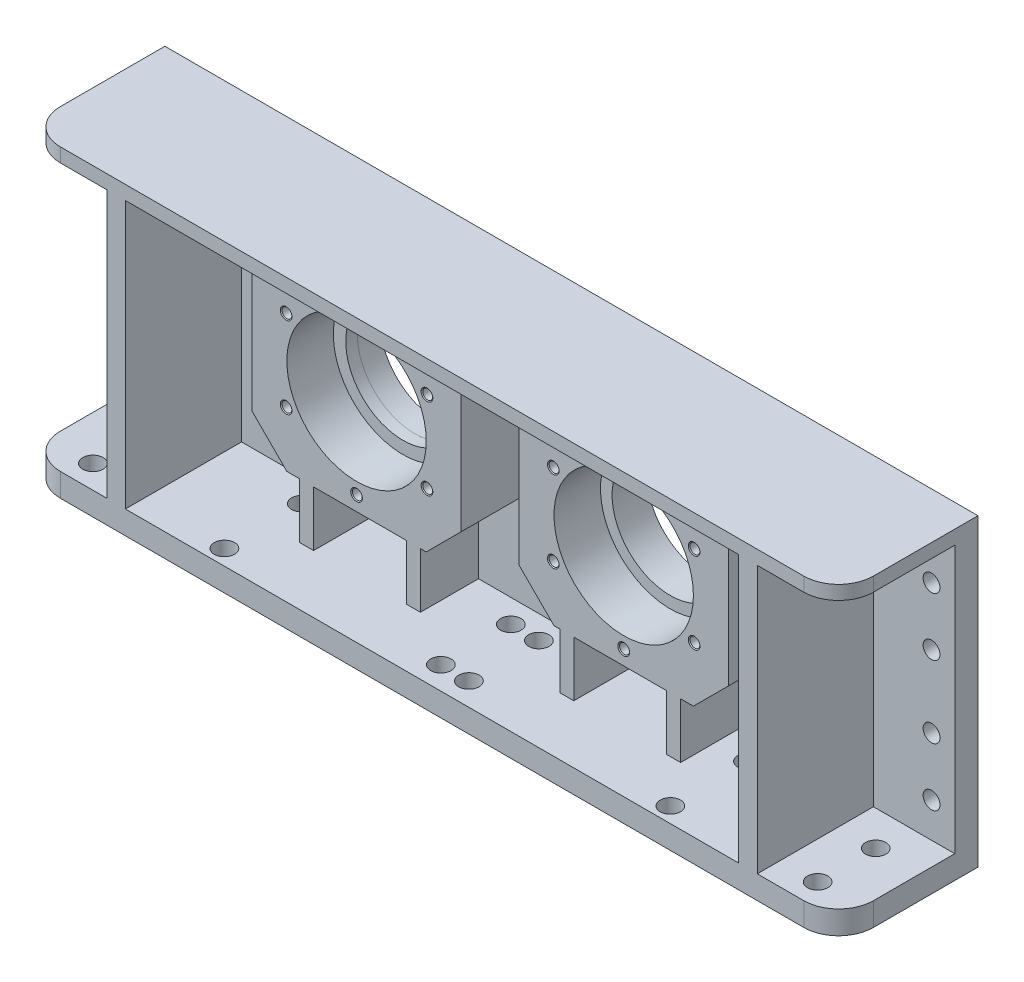
SolidWorks part; units mm, degrees
ref_plane "Front Plane" through (0, 0, 0) normal (0, 0, 1) x (1, 0, 0)
ref_plane "Top Plane" through (0, 0, 0) normal (0, 1, 0) x (1, 0, 0)
ref_plane "Right Plane" through (0, 0, 0) normal (1, 0, 0) x (0, 0, -1)
sketch "Sketch1" plane through (0, 0, 0) normal (0, 1, 0) x (1, 0, 0)
  line L0 (-55, 0) -> (55, 0) construction
  line L1 (-350, 0) -> (350, 0)
  line L2 (-350, 0) -> (-350, -120)
  line L3 (-350, -120) -> (350, -120)
  line L4 (350, 0) -> (350, -120)
  dimension "D1" = 700
  dimension "D2" = 350
  dimension "D3" = 120
extrude "Boss-Extrude1" add sketch "Sketch1" along normal blind 20
sketch "Sketch2" plane through (0, 0, 0) normal (0, 0, 1) x (1, 0, 0)
  line L1 (350, 20) -> (-350, 20)
  line L2 (350, 20) -> (350, 262)
  line L3 (350, 262) -> (-350, 262)
  line L4 (-350, 20) -> (-350, 262)
  dimension "D1" = 242
extrude "Boss-Extrude2" add sketch "Sketch2" along normal blind 20
sketch "Sketch3" plane through (0, 0, 20) normal (0, 0, 1) x (1, 0, 0)
  line L0 (350, 20) -> (350, 262) construction
  line L1 (-350, 262) -> (350, 262)
  line L2 (-350, 262) -> (-350, 250)
  line L3 (-350, 250) -> (350, 250)
  line L4 (350, 262) -> (350, 250)
  line L5 (-350, 20) -> (350, 20) construction
  line L6 (-280, 20) -> (-264, 20)
  line L7 (-280, 20) -> (-280, 250.6161)
  line L8 (-280, 250.6161) -> (-264, 250.6161)
  line L9 (-264, 20) -> (-264, 250.6161)
  line L10 (264, 20) -> (280, 20)
  line L11 (264, 20) -> (264, 251.2549)
  line L12 (264, 251.2549) -> (280, 251.2549)
  line L13 (280, 20) -> (280, 251.2549)
  line L14 (-350, 262) -> (-350, 20) construction
  line M11 (-350, 20) -> (350, 20)
  dimension "D1" = 12
  dimension "D2" = 16
  dimension "D3" = 16
  dimension "D4" = 70
  dimension "D5" = 70
extrude "Boss-Extrude3" add sketch "Sketch3" along normal up to surface (100 mm away) contours L13 L3 L11 M11 | L9 L8 L7 L6 up to face at (0, 10, 120)
sketch "Sketch4" plane through (0, 0, 20) normal (0, 0, 1) x (1, 0, 0)
  line L0 (-350, 0) -> (350, 0) construction
  line L1 (0, -66) -> (0, 66) construction
  circle A0 centre (-115, 150) radius 50
  circle A1 centre (115, 150) radius 50
  dimension "D1" = 100
  dimension "D2" = 100
  dimension "D3" = 150
  dimension "D4" = 150
  dimension "D5" = 115
  dimension "D6" = 115
extrude "Cut-Extrude1" cut sketch "Sketch4" against normal blind 30
sketch "Sketch5" plane through (0, 0, 20) normal (0, 0, 1) x (1, 0, 0)
  line L1 (-205, 232.5) -> (-25, 232.5)
  line L2 (-205, 232.5) -> (-205, 67.5)
  line L3 (-205, 67.5) -> (-25, 67.5)
  line L4 (-25, 232.5) -> (-25, 67.5)
  line L5 (-205, 232.5) -> (-25, 67.5) construction
  line L6 (-205, 67.5) -> (-25, 232.5) construction
  line L7 (25, 232.5) -> (205, 232.5)
  line L8 (25, 232.5) -> (25, 67.5)
  line L9 (25, 67.5) -> (205, 67.5)
  line L10 (205, 232.5) -> (205, 67.5)
  line L11 (25, 232.5) -> (205, 67.5) construction
  line L12 (25, 67.5) -> (205, 232.5) construction
  circle A0 centre (-115, 150) radius 49.3286
  circle A1 centre (115, 150) radius 50
  point P0 (-115, 150)
  point P5 (115, 150)
  dimension "D1" = 180
  dimension "D2" = 180
  dimension "D3" = 165
  dimension "D4" = 165
extrude "Boss-Extrude4" add sketch "Sketch5" along normal blind 50
sketch "Sketch7" plane through (0, 0, 70) normal (0, 0, 1) x (1, 0, 0)
  circle A0 centre (-115, 150) radius 60
  circle A1 centre (115, 150) radius 60
  dimension "D1" = 120
  dimension "D2" = 120
extrude "Cut-Extrude2" cut sketch "Sketch7" against normal blind 40
fillet "Fillet1" radius 30 4 edges at (350, 256, 120) (350, 10, 120) (-350, 10, 120) (-350, 256, 120)
chamfer "Chamfer1" distance 30 angle 45 8 edges at (25, 232.5, 45) (25, 67.5, 45) (205, 67.5, 45) (205, 232.5, 45) (-25, 232.5, 45) (-25, 67.5, 45) (-205, 67.5, 45) (-205, 232.5, 45)
sketch "Sketch8" plane through (0, 20, 0) normal (0, 1, 0) x (1, 0, 0)
  line L0 (-264, -20) -> (264, -20) construction
  line L5 (0, -66) -> (0, 66) construction
  line L6 (-72, -20) -> (-60, -20)
  line L7 (-72, -20) -> (-72, -70)
  line L8 (-72, -70) -> (-60, -70)
  line L9 (-60, -20) -> (-60, -70)
  line L10 (60, -20) -> (72, -20)
  line L11 (60, -20) -> (60, -70)
  line L12 (60, -70) -> (72, -70)
  line L13 (72, -20) -> (72, -70)
  line L14 (152, -20) -> (164, -20)
  line L15 (152, -20) -> (152, -70)
  line L16 (152, -70) -> (164, -70)
  line L17 (164, -20) -> (164, -70)
  line L18 (-164, -20) -> (-152, -20)
  line L19 (-164, -20) -> (-164, -70)
  line L20 (-164, -70) -> (-152, -70)
  line L21 (-152, -20) -> (-152, -70)
  dimension "D1" = 12
  dimension "D2" = 12
  dimension "D3" = 12
  dimension "D4" = 12
  dimension "D5" = 80
  dimension "D6" = 80
  dimension "D7" = 60
  dimension "D8" = 60
  dimension "D9" = 50
  dimension "D10" = 50
  dimension "D11" = 50
  dimension "D12" = 50
extrude "Boss-Extrude5" add sketch "Sketch8" along normal up to surface (47.5 mm away) up to face at (-115, 67.5, 45)
sketch "Sketch9" plane through (0, 0, 70) normal (0, 0, 1) x (1, 0, 0)
  line L0 (-115, 150) -> (-54.3782, 185) construction
  circle A0 centre (-115, 150) radius 70
  dimension "D1" = 140
hole_wizard "M10 Tapped Hole1" positions "3DSketch1" profile "Sketch10" tap size "M10" standard "ISO"
sketch3d "3DSketch1"
  point P0 (-54.3782, 185, 70)
  point P3 (-54.3782, 185, 70)
sketch "Sketch10" plane through (-54.3782, 185, 70) normal (1, 0, 0) x (0, -1, 0)
  line L0 (0, 0) -> (0, 30.0537)
  line L1 (0, 30.0537) -> (4.25, 27.5)
  line L2 (4.25, 27.5) -> (4.25, 0.6503)
  line L3 (4.25, 0.6503) -> (5.025, 0)
  line L5 (5.025, 0) -> (0, 0)
  line L6 (-4.25, 0.6503) -> (-5.025, 0) construction
  line L10 (0, 30.0537) -> (-4.25, 27.5) construction
  line L11 (0, -6.35) -> (0, 107.95) construction
  dimension "Tap Drill Dia." = 8.5
  dimension "Tap Drill Depth" = 27.5
  dimension "Near C'Sink Dia." = 10.05
  dimension "Near C'Sink Angle" = 100
  dimension "Drill Angle" = 118
cosmetic thread "Hole Thread2" parameters "D1"=20, "D2"=10
pattern_circular "CirPattern1" count 6 over 360 about axis through (-115, 150, 0) along (0, 0, 1) of "M10 Tapped Hole1"
cosmetic thread "Hole Thread3" parameters "D1"=20, "D2"=10
cosmetic thread "Hole Thread4" parameters "D1"=20, "D2"=10
cosmetic thread "Hole Thread6" parameters "D1"=20, "D2"=10
cosmetic thread "Hole Thread11" parameters "D1"=20, "D2"=10
cosmetic thread "Hole Thread12" parameters "D1"=20, "D2"=10
mirror "Mirror1" about plane through (0, 0, 0) normal (1, 0, 0) of "CirPattern1", "M10 Tapped Hole1"
cosmetic thread "Hole Thread14" parameters "D1"=20, "D2"=10
cosmetic thread "Hole Thread17" parameters "D1"=20, "D2"=10
cosmetic thread "Hole Thread19" parameters "D1"=20, "D2"=10
cosmetic thread "Hole Thread22" parameters "D1"=20, "D2"=10
cosmetic thread "Hole Thread23" parameters "D1"=20, "D2"=10
cosmetic thread "Hole Thread24" parameters "D1"=20, "D2"=10
sketch "Sketch11" plane through (0, 0, 20) normal (0, 0, 1) x (1, 0, 0)
  line L0 (350, 20) -> (350, 250) construction
  line L1 (320, 262) -> (-320, 262) construction
  line L2 (-320, 0) -> (320, 0) construction
  circle A0 centre (330, 212) radius 7.25
  circle A1 centre (330, 162) radius 7.25
  circle A2 centre (330, 100) radius 7.25
  circle A3 centre (330, 50) radius 7.25
  dimension "D1" = 14.5
  dimension "D2" = 14.5
  dimension "D3" = 14.5
  dimension "D4" = 14.5
  dimension "D5" = 20
  dimension "D6" = 20
  dimension "D7" = 20
  dimension "D8" = 20
  dimension "D9" = 50
  dimension "D10" = 50
  dimension "D11" = 50
  dimension "D12" = 50
extrude "Cut-Extrude3" cut sketch "Sketch11" against normal blind 40
sketch "Sketch12" plane through (0, 20, 0) normal (0, 1, 0) x (1, 0, 0)
  line L2 (280, -120) -> (320, -120) construction
  circle A0 centre (311.9665, -50) radius 8.75
  circle A1 centre (311.9665, -100) radius 8.75
  circle A2 centre (192.0816, -40.1059) radius 8.75
  circle A3 centre (191.9665, -106.7803) radius 8.75
  circle A4 centre (12.0816, -40.1059) radius 8.75
  circle A5 centre (12.0816, -100.3434) radius 8.75
  dimension "D1" = 17.5
  dimension "D2" = 17.5
  dimension "D3" = 17.5
  dimension "D4" = 17.5
  dimension "D5" = 17.5
  dimension "D6" = 17.5
  dimension "D7" = 20
  dimension "D8" = 50
  dimension "D9" = 120
  dimension "D10" = 180
extrude "Cut-Extrude4" cut sketch "Sketch12" against normal blind 40
mirror "Mirror3" about plane through (0, 0, 0) normal (1, 0, 0) of "Cut-Extrude3", "Cut-Extrude4"
